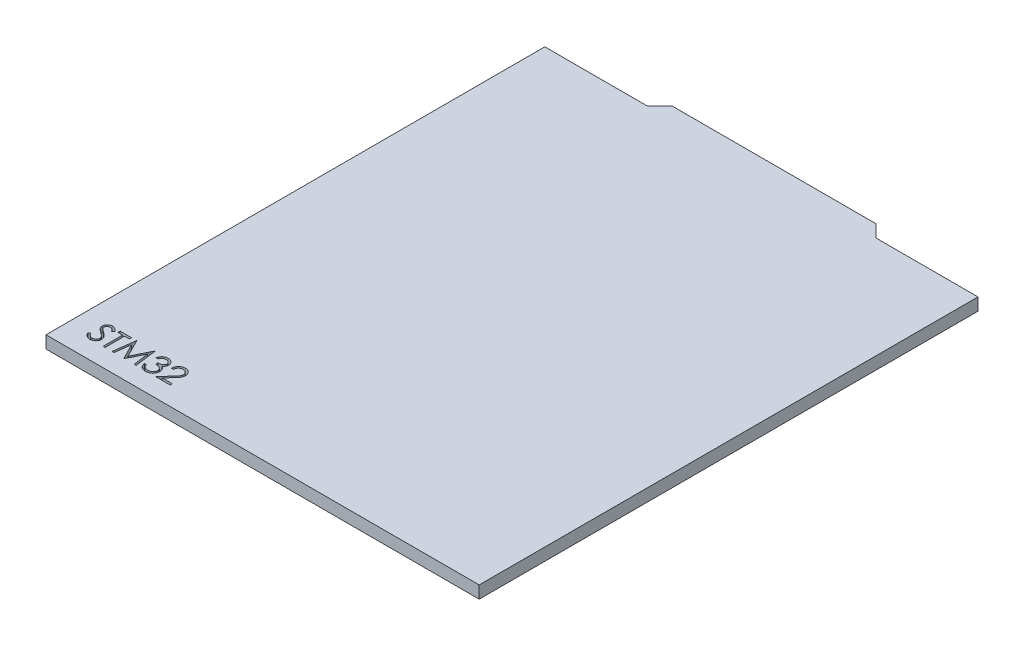
SolidWorks part; units mm, degrees
ref_plane "Alzado" through (0, 0, 0) normal (0, 0, 1) x (1, 0, 0)
ref_plane "Planta" through (0, 0, 0) normal (0, 1, 0) x (1, 0, 0)
ref_plane "Vista lateral" through (0, 0, 0) normal (1, 0, 0) x (0, 0, -1)
sketch "Sketch1" plane through (0, 0, 0) normal (0, 1, 0) x (1, 0, 0)
  line L0 (16.5, 80.6) -> (18.5, 82.6)
  line L1 (0, 0) -> (70, 0)
  line L2 (0, 0) -> (0, 80.6)
  line L3 (0, 80.6) -> (16.5, 80.6)
  line L4 (70, 0) -> (70, 80.6)
  line L5 (18.5, 82.6) -> (51.5, 82.6)
  line L6 (51.5, 82.6) -> (53.5, 80.6)
  line L7 (53.5, 80.6) -> (70, 80.6)
  point P12 (35, 82.6)
  point P13 (35, 0)
  dimension "D1" = 70
  dimension "D2" = 80.6
  dimension "D3" = 82.6
  dimension "D4" = 135
  dimension "D5" = 82.6
  dimension "D6" = 37
extrude "Boss-Extrude1" add sketch "Sketch1" along normal blind 2
sketch "Sketch2" plane through (0, 2, 0) normal (0, 1, 0) x (1, 0, 0)
  line L0 (0, 0) -> (70, 0) construction
  line L1 (0, 80.6) -> (0, 0) construction
  text T0 "STM32"
  point P1 (3.4471, 5.2809)
  dimension "D1" = 3
  dimension "D2" = 3
extrude "Cut-Extrude1" cut sketch "Sketch2" against normal blind 1
